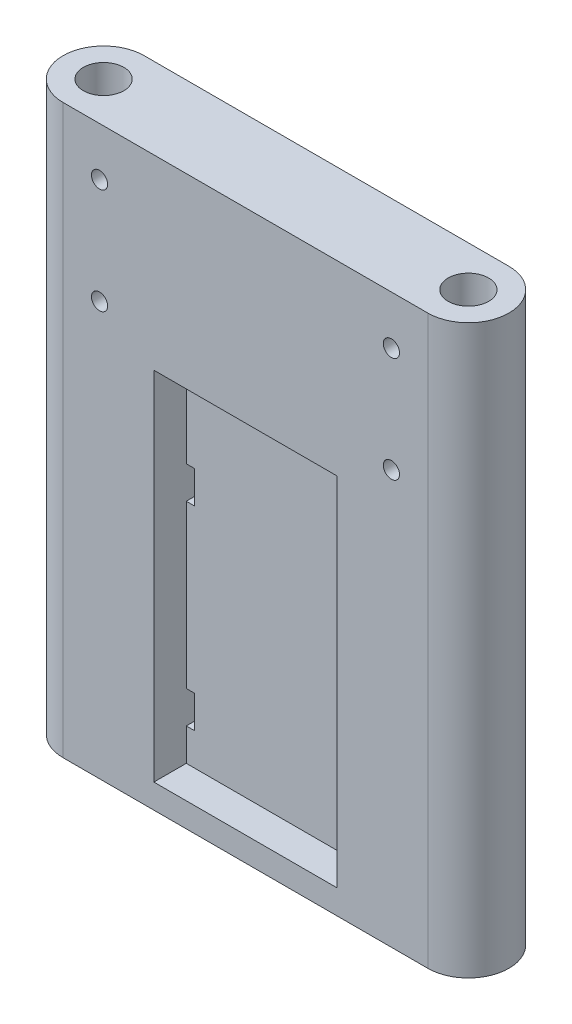
SolidWorks part; units mm, degrees
ref_plane "前视基准面" through (0, 0, 0) normal (0, 0, 1) x (1, 0, 0)
ref_plane "上视基准面" through (0, 0, 0) normal (0, 1, 0) x (1, 0, 0)
ref_plane "右视基准面" through (0, 0, 0) normal (1, 0, 0) x (0, 0, -1)
other "Configuration Table"
sketch "Sketch2" plane through (0, 0, 0) normal (0, 1, 0) x (1, 0, 0)
  line L0 (0, 0) -> (28.575, 0) construction
  line L2 (-28.575, 6.35) -> (28.575, 6.35)
  line L3 (28.575, -6.35) -> (-28.575, -6.35)
  circle A0 centre (28.575, 0) radius 3.175
  arc A1 (28.575, -6.35) -> (28.575, 6.35) centre (28.575, 0) ccw
  circle A2 centre (-28.575, 0) radius 3.175
  arc A3 (-28.575, 6.35) -> (-28.575, -6.35) centre (-28.575, 0) ccw
  dimension "D3" = 6.35
  dimension "D4" = 12.7
  dimension "D5" = 6.35
  dimension "D6" = 12.7
  dimension "D1" = 57.15
  dimension "D2" = 57.15
  dimension "D7" = 12.7
  dimension "D8" = 28.575
extrude "Boss-Extrude1" add sketch "Sketch2" along normal mid plane 88.9
sketch "Sketch5" plane through (0, 0, -6.35) normal (0, 0, -1) x (-1, 0, 0)
  line L0 (0, 36.83) -> (0, 0) construction
  line L4 (0, 6.985) -> (0, -6.985) construction
  line L5 (0, 36.83) -> (22.86, 36.83) construction
  line L6 (0, 36.83) -> (-22.86, 36.83) construction
  line L7 (22.86, 36.83) -> (22.86, 20.32) construction
  line L8 (-22.86, 36.83) -> (-22.86, 20.32) construction
  line L9 (0, 36.83) -> (0, 0) construction
  circle A0 centre (22.86, 36.83) radius 1.27
  circle A1 centre (22.86, 20.32) radius 1.27
  circle A2 centre (-22.86, 36.83) radius 1.27
  circle A3 centre (-22.86, 20.32) radius 1.27
  dimension "D4" = 16.51
  dimension "D5" = 16.51
  dimension "D6" = 2.54
  dimension "D7" = 2.54
  dimension "D8" = 2.54
  dimension "D9" = 2.54
  dimension "D1" = 22.86
  dimension "D2" = 36.83
  dimension "D3" = 22.86
extrude "Cut-Extrude1" cut sketch "Sketch5" against normal blind 5.08
sketch "Sketch6" plane through (0, 0, 6.35) normal (0, 0, 1) x (1, 0, 0)
  line L0 (0, 0) -> (0, 36.83) construction
  line L1 (0, -6.985) -> (0, 6.985) construction
  line L2 (0, 36.83) -> (22.86, 36.83) construction
  line L3 (0, 36.83) -> (-22.86, 36.83) construction
  line L4 (22.86, 36.83) -> (22.86, 20.32) construction
  line L5 (-22.86, 36.83) -> (-22.86, 20.32) construction
  circle A0 centre (22.86, 36.83) radius 1.27
  circle A1 centre (22.86, 20.32) radius 1.27
  circle A2 centre (-22.86, 36.83) radius 1.27
  circle A3 centre (-22.86, 20.32) radius 1.27
  dimension "D4" = 2.54
  dimension "D6" = 2.54
  dimension "D7" = 2.54
  dimension "D9" = 2.54
  dimension "D1" = 22.86
  dimension "D2" = 36.83
  dimension "D3" = 22.86
  dimension "D5" = 16.51
  dimension "D8" = 16.51
extrude "Cut-Extrude2" cut sketch "Sketch6" against normal blind 5.08
sketch "Sketch7" plane through (0, 0, 6.35) normal (0, 0, 1) x (1, 0, 0)
  line L0 (0, 0) -> (0, 15.24) construction
  line L1 (0, -6.985) -> (0, 6.985) construction
  line L2 (0, 15.24) -> (14.351, 15.24) construction
  line L3 (0, 15.24) -> (-14.351, 15.24) construction
  line L5 (-14.351, 15.24) -> (14.351, 15.24)
  line L6 (-14.351, 15.24) -> (-14.351, -40.64)
  line L7 (-14.351, -40.64) -> (14.351, -40.64)
  line L8 (14.351, 15.24) -> (14.351, -40.64)
  dimension "D1" = 15.24
  dimension "D2" = 14.351
  dimension "D3" = 14.351
  dimension "D4" = 55.88
extrude "Cut-Extrude3" cut sketch "Sketch7" against normal blind 5.08
mirror "Mirror1" about plane through (0, 0, 0) normal (0, 0, 1) of "Cut-Extrude3"
sketch "Sketch8" plane through (0, 0, 1.27) normal (0, 0, 1) x (1, 0, 0)
  line L0 (0, 0) -> (0, -35.56) construction
  line L1 (0, -6.985) -> (0, 6.985) construction
  line L2 (0, -35.56) -> (13.081, -35.56) construction
  line L3 (0, -35.56) -> (-13.081, -35.56) construction
  line L4 (13.081, -30.48) -> (13.081, -5.08) construction
  line L5 (13.081, -35.56) -> (14.351, -35.56)
  line L6 (13.081, -35.56) -> (13.081, -30.48)
  line L7 (13.081, -30.48) -> (14.351, -30.48)
  line L8 (14.351, -35.56) -> (14.351, -30.48)
  line L10 (13.081, -5.08) -> (14.351, -5.08)
  line L11 (13.081, -5.08) -> (13.081, 0)
  line L12 (13.081, 0) -> (14.351, 0)
  line L13 (14.351, -5.08) -> (14.351, 0)
  dimension "D1" = 35.56
  dimension "D2" = 13.081
  dimension "D3" = 13.081
  dimension "D4" = 5.08
  dimension "D5" = 1.27
  dimension "D6" = 25.4
  dimension "D7" = 5.08
  dimension "D8" = 1.27
extrude "Cut-Extrude4" cut sketch "Sketch8" against normal through all
mirror "Mirror2" about plane through (0, 0, 0) normal (1, 0, 0) of "Cut-Extrude4"
